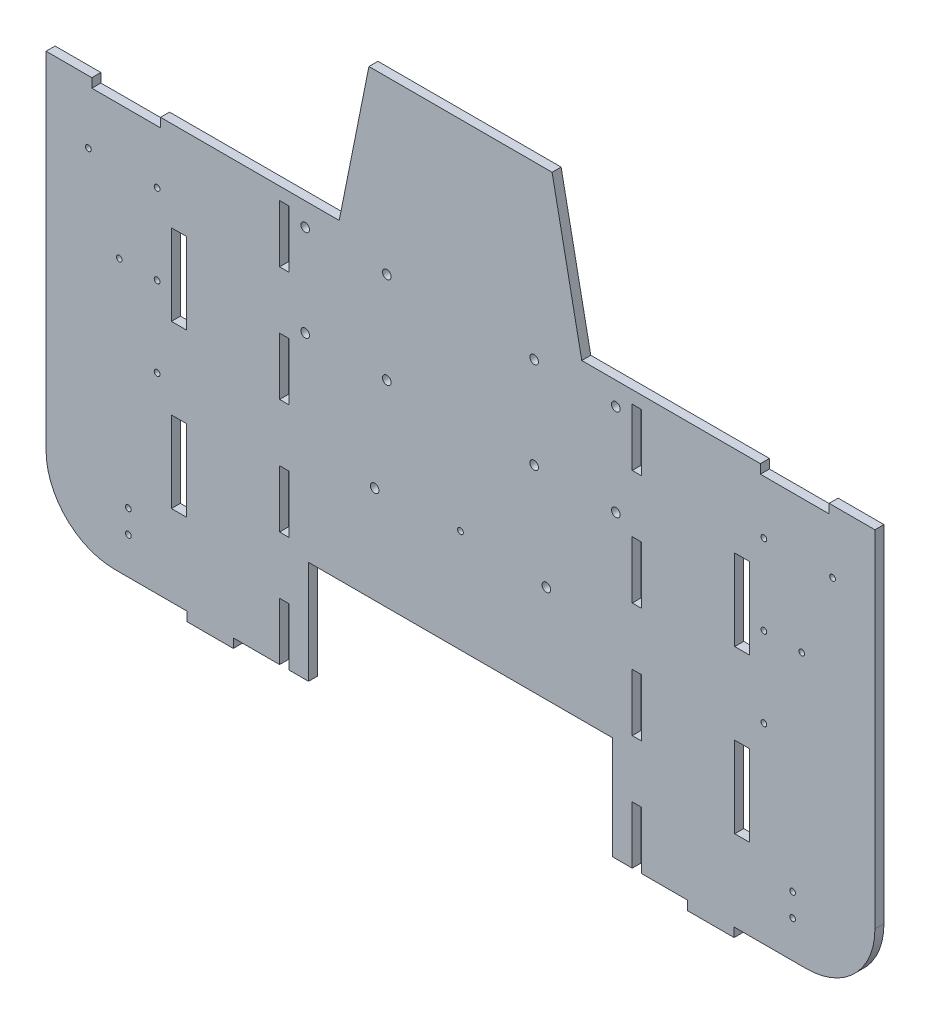
SolidWorks part; units mm, degrees
ref_plane "Front Plane" through (0, 0, 0) normal (0, 0, 1) x (1, 0, 0)
ref_plane "Top Plane" through (0, 0, 0) normal (0, 1, 0) x (1, 0, 0)
ref_plane "Right Plane" through (0, 0, 0) normal (1, 0, 0) x (0, 0, -1)
sketch "Sketch2" plane through (0, 0, 0) normal (0, 0, 1) x (1, 0, 0)
  line L0 (-408.9218, 152.7574) -> (-459.7218, 152.7574)
  line L1 (332.7218, 152.7574) -> (134.539, 152.7574)
  line L2 (-134.539, 152.7574) -> (-332.7218, 152.7574)
  line L3 (-101.6, 317.1426) -> (-134.539, 152.7574)
  line L4 (101.6, 317.1426) -> (-101.6, 317.1426)
  line L5 (-303.5218, -317.1426) -> (-303.5218, -306.9826)
  line L6 (-459.7218, 152.7574) -> (-459.7218, -230.7826)
  line L7 (459.7218, 152.7574) -> (408.9218, 152.7574)
  line L8 (-303.5218, -306.9826) -> (-383.5218, -306.9826)
  line L9 (-303.5218, -317.1426) -> (-252, -317.1426)
  line L10 (-168.529, -306.9826) -> (-190.5, -306.9826)
  line L11 (408.9218, 142.5974) -> (408.9218, 152.7574)
  line L12 (332.7218, 142.5974) -> (408.9218, 142.5974)
  line L13 (332.7218, 152.7574) -> (332.7218, 142.5974)
  line L14 (-408.9218, 142.5974) -> (-332.7218, 142.5974)
  line L15 (-408.9218, 152.7574) -> (-408.9218, 142.5974)
  line L16 (-332.7218, 142.5974) -> (-332.7218, 152.7574)
  line L17 (304.1585, -37.2346) -> (320.675, -37.2346)
  line L18 (304.1585, 52.6814) -> (304.1585, -37.2346)
  line L19 (320.675, 52.6814) -> (304.1585, 52.6814)
  line L20 (320.675, -37.2346) -> (320.675, 52.6814)
  line L21 (304.1585, -217.0666) -> (320.675, -217.0666)
  line L22 (320.675, -217.0666) -> (320.675, -127.1506)
  line L23 (320.675, -127.1506) -> (304.1585, -127.1506)
  line L24 (304.1585, -127.1506) -> (304.1585, -217.0666)
  line L25 (252, -306.9826) -> (200.66, -306.9826)
  line L26 (252, -317.1426) -> (252, -306.9826)
  line L27 (0, 317.1426) -> (0, 0) construction
  line L28 (0, 0) -> (0, -192.6826) construction
  line L30 (-320.675, -217.0666) -> (-304.1585, -217.0666)
  line L31 (-320.675, -127.1506) -> (-320.675, -217.0666)
  line L32 (-304.1585, -127.1506) -> (-320.675, -127.1506)
  line L33 (-304.1585, -217.0666) -> (-304.1585, -127.1506)
  line L34 (-304.1585, 52.6814) -> (-320.675, 52.6814)
  line L35 (-320.675, 52.6814) -> (-320.675, -37.2346)
  line L36 (-320.675, -37.2346) -> (-304.1585, -37.2346)
  line L37 (-304.1585, -37.2346) -> (-304.1585, 52.6814)
  line L38 (303.5218, -317.1426) -> (303.5218, -306.9826)
  line L39 (303.5218, -306.9826) -> (383.5218, -306.9826)
  line L40 (-252, -317.1426) -> (-252, -306.9826)
  line L41 (168.529, -306.9826) -> (168.529, -192.6826)
  line L42 (168.529, -192.6826) -> (-168.529, -192.6826)
  line L43 (-168.529, -192.6826) -> (-168.529, -306.9826)
  line L44 (-190.5, 75.1277) -> (-190.5, 11.4601) construction
  line L45 (-190.5, -52.225) -> (-190.5, -115.91) construction
  line L46 (-190.5, -179.5951) -> (-190.5, -243.2802) construction
  line L47 (190.5, 75.1277) -> (190.5, 14.3511) construction
  line L48 (190.5, -306.9826) -> (190.5, -243.2802)
  line L49 (190.5, 14.3511) -> (190.5, -115.91) construction
  line L50 (-190.5, -243.2802) -> (-190.5, -306.9826)
  line L51 (-200.66, -306.9826) -> (-252, -306.9826)
  line L52 (190.5, -115.91) -> (190.5, -243.2802) construction
  line L53 (459.7218, 152.7574) -> (459.7218, 465.1616) construction
  line L54 (190.5, -306.9826) -> (168.529, -306.9826)
  line L56 (459.7218, 152.7574) -> (459.7218, -230.7826)
  line L62 (101.6, 317.1426) -> (134.539, 152.7574)
  line L75 (200.66, -243.2802) -> (190.5, -243.2802)
  line L76 (200.66, -243.2802) -> (200.66, -306.9826)
  line L77 (-200.66, -243.2802) -> (-200.66, -306.9826)
  line L78 (-200.66, -243.2802) -> (-190.5, -243.2802)
  line L79 (200.66, -179.5951) -> (190.5, -179.5951)
  line L80 (190.5, -179.5951) -> (190.5, -115.91)
  line L81 (200.66, -115.91) -> (190.5, -115.91)
  line L82 (200.66, -115.91) -> (200.66, -179.5951)
  line L83 (190.5, -52.225) -> (190.5, 11.4601)
  line L84 (200.66, 11.4601) -> (190.5, 11.4601)
  line L85 (200.66, 11.4601) -> (200.66, -52.225)
  line L86 (200.66, -52.225) -> (190.5, -52.225)
  line L87 (200.66, 138.8128) -> (190.5, 138.8128)
  line L88 (190.5, 75.1277) -> (190.5, 138.8128)
  line L89 (200.66, 75.1277) -> (190.5, 75.1277)
  line L90 (200.66, 138.8128) -> (200.66, 75.1277)
  line L91 (-190.5, 75.1277) -> (-190.5, 138.8128)
  line L92 (-200.66, 138.8128) -> (-190.5, 138.8128)
  line L93 (-200.66, 138.8128) -> (-200.66, 75.1277)
  line L94 (-200.66, 75.1277) -> (-190.5, 75.1277)
  line L95 (-190.5, -52.225) -> (-190.5, 11.4601)
  line L96 (-200.66, 11.4601) -> (-190.5, 11.4601)
  line L97 (-200.66, 11.4601) -> (-200.66, -52.225)
  line L98 (-200.66, -52.225) -> (-190.5, -52.225)
  line L99 (-200.66, -115.91) -> (-200.66, -179.5951)
  line L100 (-200.66, -115.91) -> (-190.5, -115.91)
  line L101 (-190.5, -179.5951) -> (-190.5, -115.91)
  line L102 (-200.66, -179.5951) -> (-190.5, -179.5951)
  line L104 (252, -317.1426) -> (303.5218, -317.1426)
  arc A0 (-383.5218, -306.9826) -> (-459.7218, -230.7826) centre (-383.5218, -230.7826) cw
  arc A2 (383.5218, -306.9826) -> (459.7218, -230.7826) centre (383.5218, -230.7826) ccw
  circle A4 centre (368.427, -265.987) radius 3.175
  circle A5 centre (368.427, -240.587) radius 3.175
  circle A6 centre (336.5503, -94.6874) radius 3.175
  circle A7 centre (378.5738, -5.7874) radius 3.175
  circle A8 centre (336.5503, -5.7874) radius 3.175
  circle A9 centre (336.5503, 83.1126) radius 3.175
  circle A10 centre (412.7503, 83.1126) radius 3.175
  circle A11 centre (-412.7503, 83.1126) radius 3.175
  circle A12 centre (-336.5503, 83.1126) radius 3.175
  circle A13 centre (-336.5503, -5.7874) radius 3.175
  circle A14 centre (-378.5738, -5.7874) radius 3.175
  circle A15 centre (-336.5503, -94.6874) radius 3.175
  circle A16 centre (-368.427, -240.587) radius 3.175
  circle A17 centre (-368.427, -265.987) radius 3.175
  circle A18 centre (172.2755, 127.3574) radius 4.7625
  circle A19 centre (172.2755, 25.7574) radius 4.7625
  circle A20 centre (81.7245, 25.7574) radius 4.7625
  circle A21 centre (81.7245, 127.3574) radius 4.7625
  circle A22 centre (-81.7245, 25.7574) radius 4.7625
  circle A23 centre (-81.7245, 127.3574) radius 4.7625
  circle A24 centre (-172.2755, 127.3574) radius 4.7625
  circle A25 centre (-172.2755, 25.7574) radius 4.7625
  circle A26 centre (0, -78.3826) radius 3.175
  circle A27 centre (-95.25, -84.7326) radius 4.7625
  circle A28 centre (95.25, -84.7326) radius 4.7625
  dimension "D1" = 76.2
  dimension "D8" = 76.2
  dimension "D2" = 10.16
  dimension "D3" = 919.4436
  dimension "D4" = 139.0468
  dimension "D5" = 252
  dimension "D6" = 317.1426
  dimension "D7" = 152.7574
  dimension "D9" = 168.529
  dimension "D10" = 80
  dimension "D11" = 51.5218
  dimension "D12" = 10.16
  dimension "D13" = 190.5
  dimension "D14" = 190.5
  dimension "D15" = 50.8
  dimension "D17" = 50.8
  dimension "D18" = 76.2
extrude "Boss-Extrude1" add sketch "Sketch2" against normal blind 10
